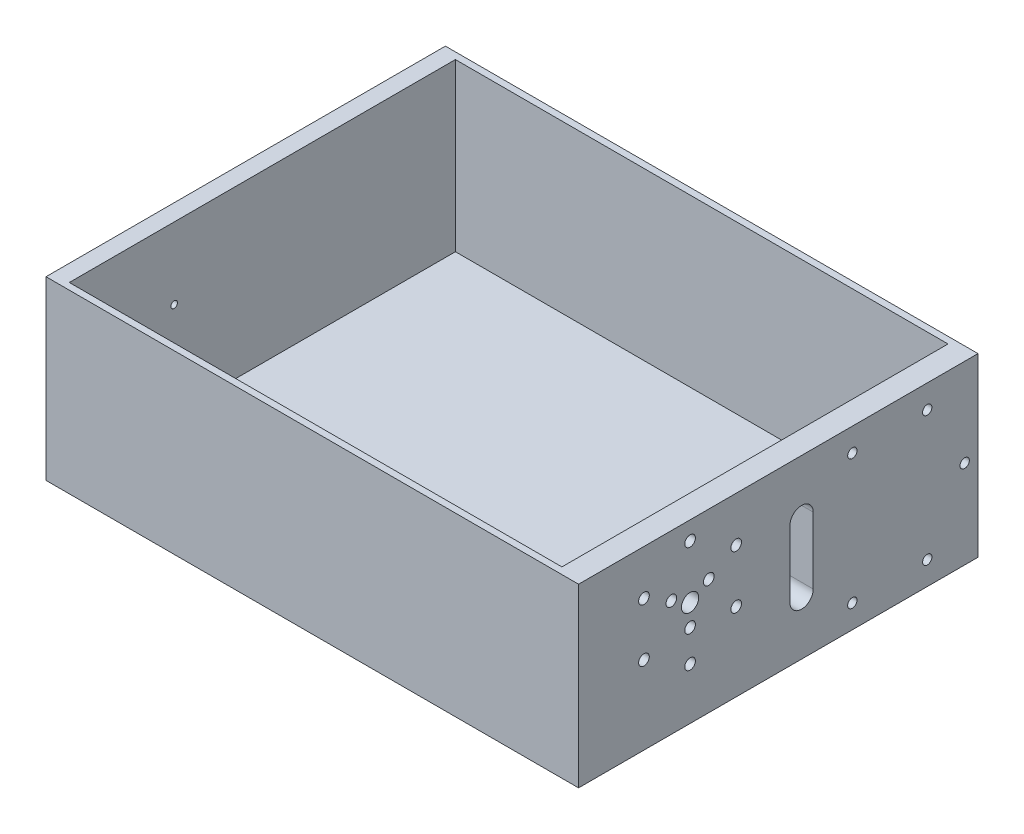
SolidWorks part; units mm, degrees
ref_plane "Front Plane" through (0, 0, 0) normal (0, 0, 1) x (1, 0, 0)
ref_plane "Top Plane" through (0, 0, 0) normal (0, 1, 0) x (1, 0, 0)
ref_plane "Right Plane" through (0, 0, 0) normal (1, 0, 0) x (0, 0, -1)
sketch "Sketch1" plane through (0, 0, 0) normal (0, 1, 0) x (1, 0, 0)
  line L1 (-80, -60) -> (80, -60)
  line L2 (-80, -60) -> (-80, 60)
  line L3 (-80, 60) -> (80, 60)
  line L4 (80, -60) -> (80, 60)
  line L5 (-80, -60) -> (80, 60) construction
  line L6 (-80, 60) -> (80, -60) construction
  point P0 (0, 0)
  dimension "D1" = 160
  dimension "D2" = 120
extrude "Boss-Extrude1" add sketch "Sketch1" along normal blind 3
sketch "Sketch2" plane through (0, 3, 0) normal (0, 1, 0) x (1, 0, 0)
  line L1 (-75, 58) -> (73, 58)
  line L2 (-75, 58) -> (-75, -58)
  line L3 (-75, -58) -> (73, -58)
  line L4 (80, -60) -> (80, 60)
  line L5 (80, 60) -> (-80, 60)
  line L6 (-80, 60) -> (-80, -60)
  line L7 (-80, -60) -> (80, -60)
  line L8 (80, -60) -> (80, 60)
  line L9 (80, 60) -> (-80, 60)
  line L10 (-80, 60) -> (-80, -60)
  line L11 (-80, -60) -> (80, -60)
  line L12 (73, 58) -> (73, -58)
  dimension "D2" = 7
  dimension "D3" = 2
  dimension "D4" = 2
  dimension "D5" = 5
  dimension "D1" = 0
extrude "Boss-Extrude2" add sketch "Sketch2" along normal blind 50
sketch "Sketch3" plane through (80, 0, 0) normal (1, 0, 0) x (0, 0, -1)
  line L0 (33.5, 26.5) -> (-26.5, 26.5) construction
  line L1 (-26.5, 26.5) -> (-26.5, 31.5) construction
  circle A0 centre (-26.5, 31.5) radius 1
  dimension "D3" = 2
  dimension "D1" = 60
  dimension "D2" = 5
extrude "Cut-Extrude1" cut sketch "Sketch3" against normal through all
sketch "Sketch4" plane through (73, 0, 0) normal (-1, 0, 0) x (0, 0, 1)
  circle A0 centre (26.5, 25) radius 1.6 construction
  circle A1 centre (32.1292, 34.75) radius 1.6 construction
  circle A2 centre (20.8708, 34.75) radius 1.6 construction
  circle A3 centre (26.5, 31.5) radius 2.6 construction
  circle A4 centre (26.5, 47.5) radius 1.6 construction
  circle A5 centre (12.6436, 39.5) radius 1.6 construction
  circle A6 centre (12.6436, 23.5) radius 1.6 construction
  circle A7 centre (26.5, 15.5) radius 1.6 construction
  circle A8 centre (40.3564, 23.5) radius 1.6 construction
  circle A9 centre (40.3564, 39.5) radius 1.6 construction
  circle A10 centre (26.5, 25) radius 1.6
  circle A11 centre (32.1292, 34.75) radius 1.6
  circle A12 centre (20.8708, 34.75) radius 1.6
  circle A13 centre (26.5, 31.5) radius 2.6
  circle A14 centre (26.5, 47.5) radius 1.6
  circle A15 centre (12.6436, 39.5) radius 1.6
  circle A16 centre (12.6436, 23.5) radius 1.6
  circle A17 centre (26.5, 15.5) radius 1.6
  circle A18 centre (40.3564, 23.5) radius 1.6
  circle A19 centre (40.3564, 39.5) radius 1.6
  arc A20 (-21.225, 7.0144) -> (-23.275, 7.0144) centre (-22.25, 7.0144) ccw construction
  arc A21 (-43.725, 7.0144) -> (-45.775, 7.0144) centre (-44.75, 7.0144) ccw construction
  arc A22 (-54.975, 26.5) -> (-57.025, 26.5) centre (-56, 26.5) ccw construction
  arc A23 (-43.725, 45.9856) -> (-45.775, 45.9856) centre (-44.75, 45.9856) ccw construction
  arc A24 (-21.225, 45.9856) -> (-23.275, 45.9856) centre (-22.25, 45.9856) ccw construction
  arc A25 (-21.225, 7.0144) -> (-23.275, 7.0144) centre (-22.25, 7.0144) ccw construction
  arc A26 (-43.725, 7.0144) -> (-45.775, 7.0144) centre (-44.75, 7.0144) ccw construction
  arc A27 (-54.975, 26.5) -> (-57.025, 26.5) centre (-56, 26.5) ccw construction
  arc A28 (-43.725, 45.9856) -> (-45.775, 45.9856) centre (-44.75, 45.9856) ccw construction
  arc A29 (-21.225, 45.9856) -> (-23.275, 45.9856) centre (-22.25, 45.9856) ccw construction
  circle A30 centre (-22.25, 45.9856) radius 1.4
  circle A31 centre (-44.75, 45.9856) radius 1.4
  circle A32 centre (-56, 26.5) radius 1.4
  circle A33 centre (-44.75, 7.0144) radius 1.4
  circle A34 centre (-22.25, 7.0144) radius 1.4
  dimension "D1" = 2.8
extrude "Cut-Extrude2" cut sketch "Sketch4" against normal through all
sketch "Sketch5" plane through (73, 0, 0) normal (-1, 0, 0) x (0, 0, 1)
  line L85 (9.8936, 36.75) -> (15.3936, 36.75)
  line L86 (9.8936, 36.75) -> (9.8936, 42.25)
  line L87 (9.8936, 42.25) -> (15.3936, 42.25)
  line L88 (15.3936, 36.75) -> (15.3936, 42.25)
  line L89 (9.8936, 36.75) -> (15.3936, 42.25) construction
  line L90 (9.8936, 42.25) -> (15.3936, 36.75) construction
  line L91 (23.75, 44.75) -> (29.25, 44.75)
  line L92 (23.75, 44.75) -> (23.75, 50.25)
  line L93 (23.75, 50.25) -> (29.25, 50.25)
  line L94 (29.25, 44.75) -> (29.25, 50.25)
  line L95 (23.75, 44.75) -> (29.25, 50.25) construction
  line L96 (23.75, 50.25) -> (29.25, 44.75) construction
  line L97 (18.1208, 32) -> (23.6208, 32)
  line L98 (18.1208, 32) -> (18.1208, 37.5)
  line L99 (18.1208, 37.5) -> (23.6208, 37.5)
  line L100 (23.6208, 32) -> (23.6208, 37.5)
  line L101 (18.1208, 32) -> (23.6208, 37.5) construction
  line L102 (18.1208, 37.5) -> (23.6208, 32) construction
  line L103 (9.8936, 20.75) -> (15.3936, 20.75)
  line L104 (9.8936, 20.75) -> (9.8936, 26.25)
  line L105 (9.8936, 26.25) -> (15.3936, 26.25)
  line L106 (15.3936, 20.75) -> (15.3936, 26.25)
  line L107 (9.8936, 20.75) -> (15.3936, 26.25) construction
  line L108 (9.8936, 26.25) -> (15.3936, 20.75) construction
  line L109 (23.75, 12.75) -> (29.25, 12.75)
  line L110 (23.75, 12.75) -> (23.75, 18.25)
  line L111 (23.75, 18.25) -> (29.25, 18.25)
  line L112 (29.25, 12.75) -> (29.25, 18.25)
  line L113 (23.75, 12.75) -> (29.25, 18.25) construction
  line L114 (23.75, 18.25) -> (29.25, 12.75) construction
  line L115 (23.75, 22.25) -> (29.25, 22.25)
  line L116 (23.75, 22.25) -> (23.75, 27.75)
  line L117 (23.75, 27.75) -> (29.25, 27.75)
  line L118 (29.25, 22.25) -> (29.25, 27.75)
  line L119 (23.75, 22.25) -> (29.25, 27.75) construction
  line L120 (23.75, 27.75) -> (29.25, 22.25) construction
  line L121 (37.6064, 20.75) -> (43.1064, 20.75)
  line L122 (37.6064, 20.75) -> (37.6064, 26.25)
  line L123 (37.6064, 26.25) -> (43.1064, 26.25)
  line L124 (43.1064, 20.75) -> (43.1064, 26.25)
  line L125 (37.6064, 20.75) -> (43.1064, 26.25) construction
  line L126 (37.6064, 26.25) -> (43.1064, 20.75) construction
  line L127 (29.3792, 32) -> (34.8792, 32)
  line L128 (29.3792, 32) -> (29.3792, 37.5)
  line L129 (29.3792, 37.5) -> (34.8792, 37.5)
  line L130 (34.8792, 32) -> (34.8792, 37.5)
  line L131 (29.3792, 32) -> (34.8792, 37.5) construction
  line L132 (29.3792, 37.5) -> (34.8792, 32) construction
  line L133 (37.6064, 36.75) -> (43.1064, 36.75)
  line L134 (37.6064, 36.75) -> (37.6064, 42.25)
  line L135 (37.6064, 42.25) -> (43.1064, 42.25)
  line L136 (43.1064, 36.75) -> (43.1064, 42.25)
  line L137 (37.6064, 36.75) -> (43.1064, 42.25) construction
  line L138 (37.6064, 42.25) -> (43.1064, 36.75) construction
  point P0 (12.6436, 39.5)
  point P5 (26.5, 47.5)
  point P10 (20.8708, 34.75)
  point P15 (12.6436, 23.5)
  point P20 (26.5, 15.5)
  point P25 (26.5, 25)
  point P30 (40.3564, 23.5)
  point P35 (32.1292, 34.75)
  point P40 (40.3564, 39.5)
  dimension "D1" = 5.5
extrude "Nut cavities" cut sketch "Sketch5" against normal blind 2.5
sketch "Sketch8" plane through (80, 0, 0) normal (1, 0, 0) x (0, 0, -1)
  line L0 (7, 36.5) -> (7, 16.5) construction
  line L1 (10.5, 36.5) -> (10.5, 16.5)
  line L2 (3.5, 36.5) -> (3.5, 16.5)
  line L3 (33.5, 26.5) -> (7, 26.5) construction
  arc A0 (10.5, 36.5) -> (3.5, 36.5) centre (7, 36.5) ccw
  arc A1 (3.5, 16.5) -> (10.5, 16.5) centre (7, 16.5) ccw
  point P2 (7, 26.5)
  dimension "D1" = 7
  dimension "D2" = 20
  dimension "D3" = 26.5
extrude "Cut-Extrude3" cut sketch "Sketch8" against normal blind 10 contours L2 A1 L1 A0
